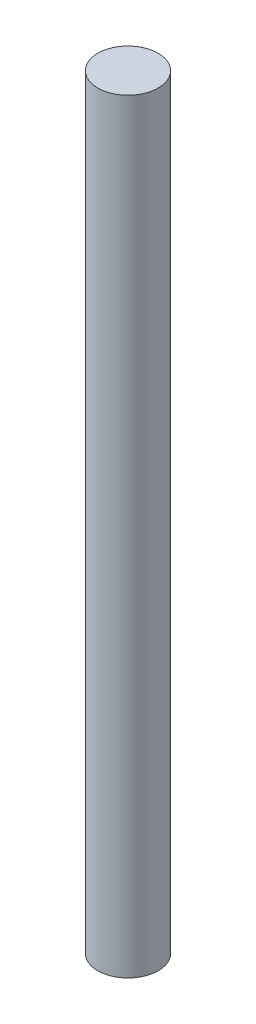
SolidWorks part; units mm, degrees
ref_plane "Front" through (0, 0, 0) normal (0, 0, 1) x (1, 0, 0)
ref_plane "Top" through (0, 0, 0) normal (0, 1, 0) x (1, 0, 0)
ref_plane "Right" through (0, 0, 0) normal (1, 0, 0) x (0, 0, -1)
sketch "草图1" plane through (0, 0, 0) normal (0, 1, 0) x (1, 0, 0)
  circle A0 centre (0, 0) radius 1.5
extrude "凸台-拉伸1" add sketch "草图1" along normal blind 38
move or copy body "实体-移动/复制1" [suppressed] bodies to move or copy 101
